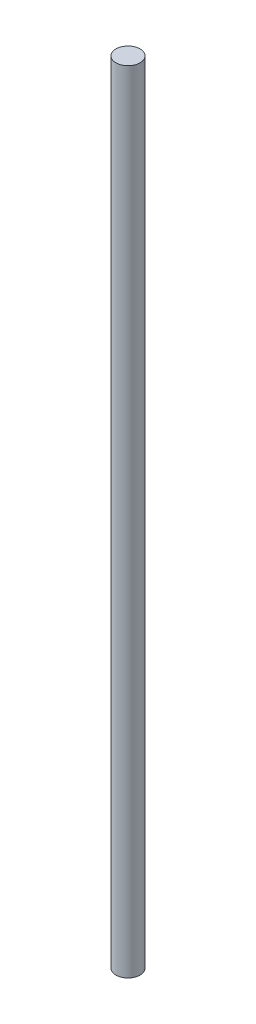
SolidWorks part; units mm, degrees
ref_plane "Front Plane" through (0, 0, 0) normal (0, 0, 1) x (1, 0, 0)
ref_plane "Top Plane" through (0, 0, 0) normal (0, 1, 0) x (1, 0, 0)
ref_plane "Right Plane" through (0, 0, 0) normal (1, 0, 0) x (0, 0, -1)
sketch "Sketch1" plane through (0, 0, 0) normal (0, 1, 0) x (1, 0, 0)
  circle A0 centre (0, 0) radius 0.55
  dimension "D1" = 1.1
extrude "Boss-Extrude1" add sketch "Sketch1" along normal blind 36
